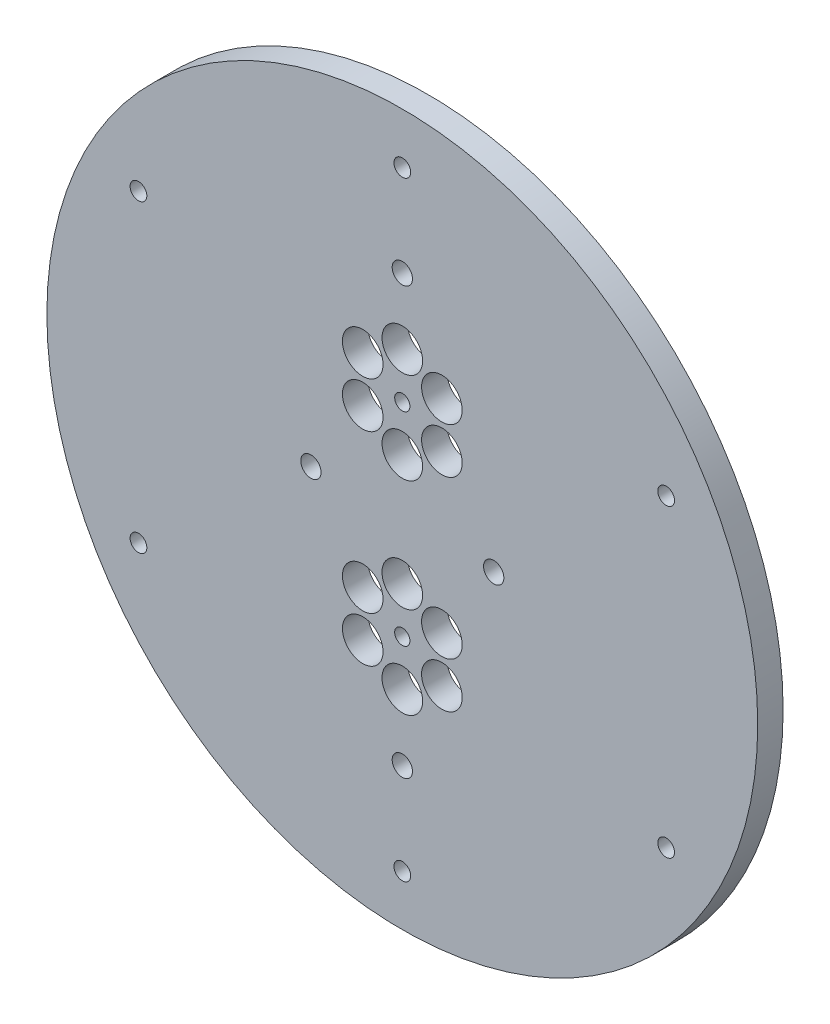
SolidWorks part; units mm, degrees
ref_plane "Front Plane" through (0, 0, 0) normal (0, 0, 1) x (1, 0, 0)
ref_plane "Top Plane" through (0, 0, 0) normal (0, 1, 0) x (1, 0, 0)
ref_plane "Right Plane" through (0, 0, 0) normal (1, 0, 0) x (0, 0, -1)
sketch "Sketch1" plane through (0, 0, 0) normal (0, 0, 1) x (1, 0, 0)
  line L0 (0, 70) -> (0, -70) construction
  line L1 (0, 0) -> (70, 0) construction
  circle A0 centre (0, 0) radius 70
  circle A2 centre (0, 0) radius 60 construction
  circle A3 centre (0, 60) radius 1.65
  circle A4 centre (51.9615, 30) radius 1.65
  circle A5 centre (51.9615, -30) radius 1.65
  circle A6 centre (0, -60) radius 1.65
  circle A7 centre (-51.9615, -30) radius 1.65
  circle A8 centre (-51.9615, 30) radius 1.65
  circle A9 centre (0, 0) radius 9 construction
  circle A10 centre (0, 0) radius 1.5 construction
  circle A11 centre (0, 9) radius 4 construction
  circle A12 centre (7.7942, 4.5) radius 4 construction
  circle A13 centre (7.7942, -4.5) radius 4 construction
  circle A14 centre (0, -9) radius 4 construction
  circle A15 centre (-7.7942, -4.5) radius 4 construction
  circle A16 centre (-7.7942, 4.5) radius 4 construction
  circle A17 centre (0, 20) radius 9 construction
  circle A18 centre (0, 29) radius 4
  circle A19 centre (7.7942, 24.5) radius 4
  circle A20 centre (7.7942, 15.5) radius 4
  circle A21 centre (0, 11) radius 4
  circle A22 centre (-7.7942, 15.5) radius 4
  circle A23 centre (-7.7942, 24.5) radius 4
  circle A24 centre (0, 20) radius 1.5
  circle A25 centre (7.7942, -15.5) radius 4
  circle A26 centre (0, -11) radius 4
  circle A27 centre (-7.7942, -15.5) radius 4
  circle A28 centre (0, -20) radius 1.5
  circle A29 centre (-7.7942, -24.5) radius 4
  circle A30 centre (0, -29) radius 4
  circle A31 centre (7.7942, -24.5) radius 4
  circle A32 centre (0, 0) radius 13 construction
  point P19 (0, 0)
  point P33 (0, 0)
  point P51 (0, 20)
  dimension "D1" = 140
  dimension "D2" = 18
  dimension "D3" = 10
  dimension "D4" = 3.3
  dimension "D6" = 6
  dimension "D7" = 8
  dimension "D8" = 3
  dimension "D9" = 18
  dimension "D12" = 26
  dimension "D10" = 20
  dimension "D5" = 6
  dimension "D11" = 6
extrude "Boss-Extrude1" add sketch "Sketch1" along normal blind 5
sketch "Sketch2" plane through (0, 0, 5) normal (0, 0, 1) x (1, 0, 0)
  line L0 (0, 0) -> (0, 37.6692) construction
  line L1 (0, 0) -> (16.9313, 0) construction
  circle A0 centre (0, 42) radius 2
  circle A1 centre (0, -42) radius 2
  circle A2 centre (18, 0) radius 2
  circle A3 centre (-18, 0) radius 2
  point P11 (0, 0)
  dimension "D1" = 4
  dimension "D2" = 36
  dimension "D3" = 84
extrude "Cut-Extrude1" cut sketch "Sketch2" against normal through all
